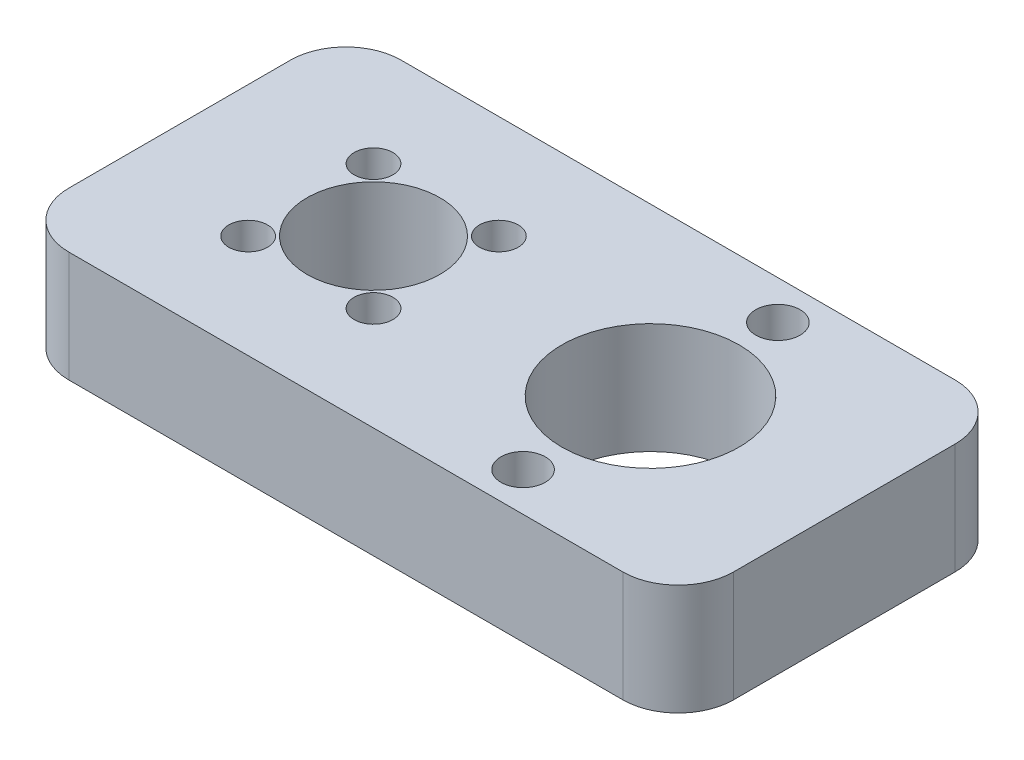
SolidWorks part; units mm, degrees
ref_plane "Front Plane" through (0, 0, 0) normal (0, 0, 1) x (1, 0, 0)
ref_plane "Top Plane" through (0, 0, 0) normal (0, 1, 0) x (1, 0, 0)
ref_plane "Right Plane" through (0, 0, 0) normal (1, 0, 0) x (0, 0, -1)
sketch "Sketch1" plane through (0, 0, 0) normal (0, 1, 0) x (1, 0, 0)
  line L0 (-12.5, 0) -> (-30, 0) construction
  line L1 (-30, 15) -> (30, 15)
  line L2 (-30, 15) -> (-30, -15)
  line L3 (-30, -15) -> (30, -15)
  line L4 (30, 15) -> (30, -15)
  line L5 (-30, 15) -> (30, -15) construction
  line L6 (-30, -15) -> (30, 15) construction
  line L7 (-18.1569, 5.6569) -> (-12.5, 0) construction
  line L8 (12.5, -11.5) -> (12.5, 11.5) construction
  circle A0 centre (-12.5, 0) radius 8 construction
  circle A5 centre (12.5, 0) radius 8
  circle A6 centre (-12.5, 0) radius 6
  circle A7 centre (-18.1569, 5.6569) radius 1.75
  circle A8 centre (-6.8431, 5.6569) radius 1.75
  circle A9 centre (-6.8431, -5.6569) radius 1.75
  circle A10 centre (-18.1569, -5.6569) radius 1.75
  circle A11 centre (12.5, -11.5) radius 2
  circle A12 centre (12.5, 11.5) radius 2
  point P0 (0, 0)
  point P23 (12.5, 0)
  dimension "D3" = 16
  dimension "D5" = 3.5
  dimension "D7" = 16
  dimension "D9" = 12
  dimension "D12" = 4
  dimension "D1" = 30
  dimension "D2" = 60
  dimension "D4" = 12.5
  dimension "D8" = 25
  dimension "D6" = 45
  dimension "D11" = 11.5
  dimension "D10" = 4
extrude "Boss-Extrude1" add sketch "Sketch1" along normal blind 10
fillet "Fillet1" radius 5 4 edges at (30, 5, 15) (-30, 5, 15) (-30, 5, -15) (30, 5, -15)
